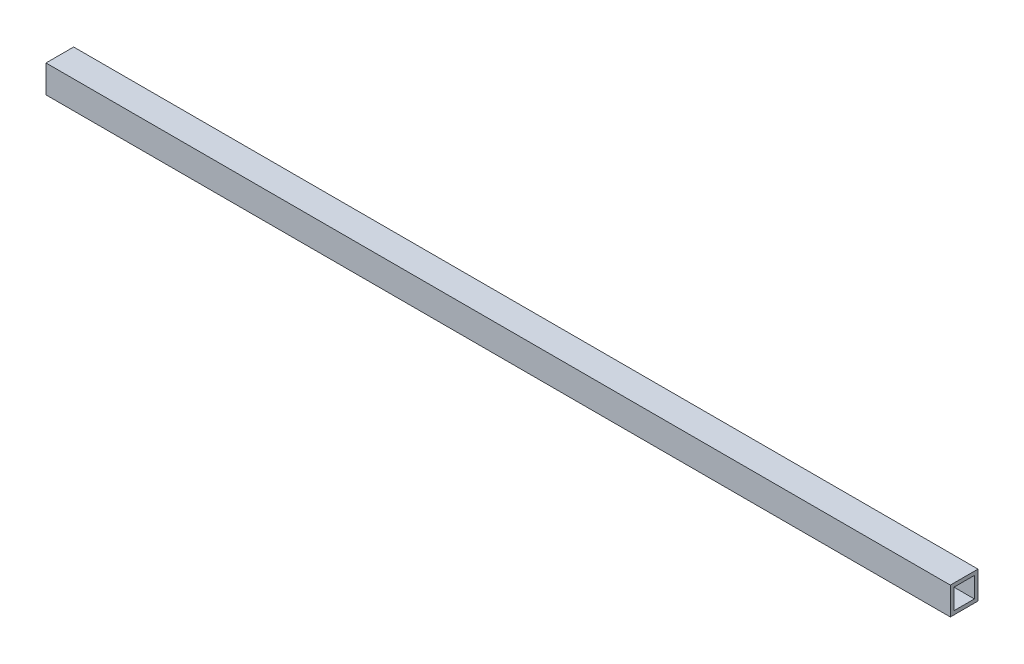
SolidWorks part; units mm, degrees
ref_plane "Front Plane" through (0, 0, 0) normal (0, 0, 1) x (1, 0, 0)
ref_plane "Top Plane" through (0, 0, 0) normal (0, 1, 0) x (1, 0, 0)
ref_plane "Right Plane" through (0, 0, 0) normal (1, 0, 0) x (0, 0, -1)
sketch "Sketch1" plane through (0, 0, 0) normal (1, 0, 0) x (0, 0, -1)
  line L0 (5, 5) -> (5, 33)
  line L1 (0, 0) -> (38, 0)
  line L2 (0, 0) -> (0, 38)
  line L3 (0, 38) -> (38, 38)
  line L4 (38, 0) -> (38, 38)
  line L5 (5, 33) -> (33, 33)
  line L6 (33, 5) -> (33, 33)
  line L7 (5, 5) -> (33, 5)
  dimension "D1" = 38
  dimension "D2" = 38
  dimension "D3" = 5
extrude "Boss-Extrude1" add sketch "Sketch1" along normal blind 1242
